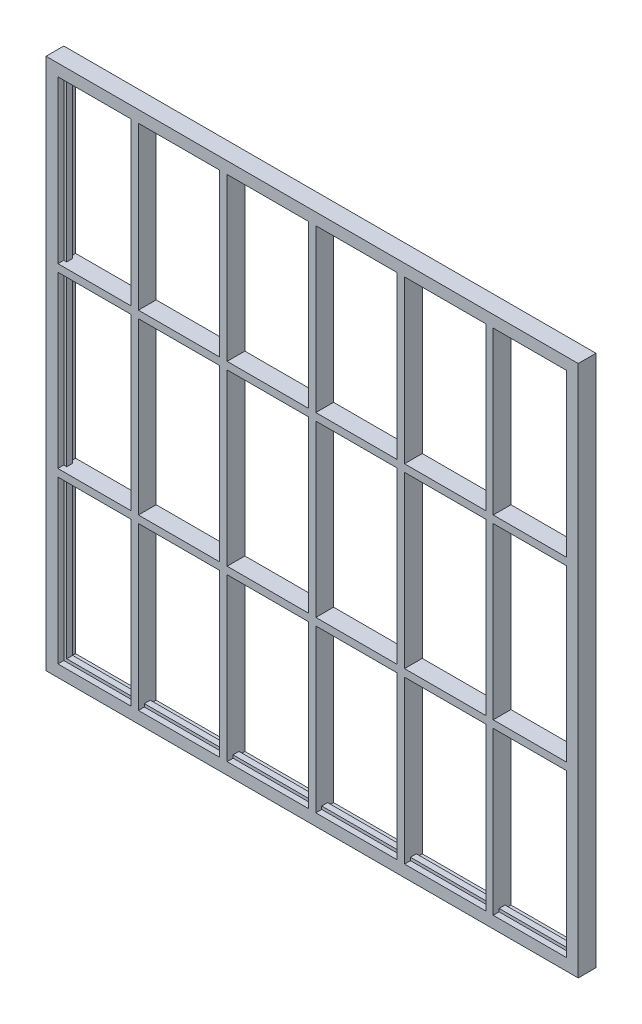
SolidWorks part; units mm, degrees
ref_plane "前视基准面" through (0, 0, 0) normal (0, 0, 1) x (1, 0, 0)
ref_plane "上视基准面" through (0, 0, 0) normal (0, 1, 0) x (1, 0, 0)
ref_plane "右视基准面" through (0, 0, 0) normal (1, 0, 0) x (0, 0, -1)
sketch "草图1" plane through (0, 0, 0) normal (1, 0, 0) x (0, 0, -1)
  line L0 (30, 0) -> (-30, 0)
  line L1 (-30, 0) -> (-30, 40)
  line L2 (-30, 40) -> (-10, 40)
  line L3 (-10, 40) -> (-10, 50)
  line L4 (-10, 50) -> (10, 50)
  line L5 (0, 0) -> (0, 164.1985) construction
  line L6 (10, 40) -> (10, 50)
  line L7 (30, 40) -> (10, 40)
  line L8 (30, 0) -> (30, 40)
  line L9 (-155.4817, 900) -> (236.5603, 900) construction
  line L10 (30, 1800) -> (30, 1760)
  line L11 (30, 1760) -> (10, 1760)
  line L12 (10, 1760) -> (10, 1750)
  line L13 (-10, 1750) -> (10, 1750)
  line L14 (-10, 1760) -> (-10, 1750)
  line L15 (-30, 1760) -> (-10, 1760)
  line L16 (-30, 1800) -> (-30, 1760)
  line L17 (30, 1800) -> (-30, 1800)
  point P9 (0, 50)
  point P22 (0, 1750)
  dimension "D1" = 60
  dimension "D2" = 40
  dimension "D3" = 50
  dimension "D4" = 900
  dimension "D5" = 20
extrude "凸台-拉伸1" add sketch "草图1" along normal mid plane 1800
sketch "草图3" plane through (0, 1760, 0) normal (0, -1, 0) x (1, 0, 0)
  line L0 (-900, -30) -> (-900, 30)
  line L1 (-900, 30) -> (-860, 30)
  line L2 (900, 30) -> (-900, 30) construction
  line L3 (-860, 30) -> (-860, 10)
  line L4 (-860, 10) -> (-850, 10)
  line L5 (-850, 10) -> (-850, -10)
  line L6 (-850, -10) -> (-860, -10)
  line L7 (-860, -10) -> (-860, -30)
  line L8 (900, -30) -> (-900, -30) construction
  line L9 (-860, -30) -> (-900, -30)
  line L10 (-900, 0) -> (-1150.2083, 0) construction
  line L11 (0, 0) -> (0, 199.5388) construction
  line L12 (900, 0) -> (1150.2083, 0) construction
  line L13 (860, -30) -> (900, -30)
  line L14 (860, -10) -> (860, -30)
  line L15 (850, -10) -> (860, -10)
  line L16 (850, 10) -> (850, -10)
  line L17 (860, 10) -> (850, 10)
  line L18 (860, 30) -> (860, 10)
  line L19 (900, 30) -> (860, 30)
  line L20 (900, -30) -> (900, 30)
  dimension "D1" = 40
  dimension "D2" = 50
  dimension "D3" = 20
extrude "凸台-拉伸2" add sketch "草图3" along normal up to surface (1720 mm away) separate body up to face at (0, 40, 20)
sketch "草图4" plane through (0, 1760, 0) normal (0, -1, 0) x (1, 0, 0)
  line L0 (900, -30) -> (-900, -30) construction
  line L1 (-900, 30) -> (-850, 30)
  line L2 (-900, 30) -> (-900, -30)
  line L3 (-900, -30) -> (-850, -30)
  line L4 (-850, 30) -> (-850, -30)
  line L5 (0, 0) -> (0, 218.547) construction
  line L6 (850, 30) -> (850, -30)
  line L7 (900, -30) -> (850, -30)
  line L8 (900, 30) -> (900, -30)
  line L9 (900, 30) -> (850, 30)
  dimension "D1" = 50
extrude "切除-拉伸1" cut sketch "草图4" along normal blind 10
sketch "草图5" plane through (0, 40, 0) normal (0, 1, 0) x (1, 0, 0)
  line L0 (900, -30) -> (-900, -30) construction
  line L1 (-900, 30) -> (-850, 30)
  line L2 (-900, 30) -> (-900, -30)
  line L3 (-900, -30) -> (-850, -30)
  line L4 (-850, 30) -> (-850, -30)
  line L5 (0, 0) -> (0, 304.5992) construction
  line L6 (850, 30) -> (850, -30)
  line L7 (900, -30) -> (850, -30)
  line L8 (900, 30) -> (900, -30)
  line L9 (900, 30) -> (850, 30)
  dimension "50" = 50
extrude "切除-拉伸2" cut sketch "草图5" along normal blind 10
sketch "草图6" plane through (860, 0, 0) normal (-1, 0, 0) x (0, 0, 1)
  line L0 (30, 40) -> (30, 1760) construction
  line L1 (-30, 1212.5) -> (30, 1212.5)
  line L2 (-30, 1212.5) -> (-30, 1187.5)
  line L3 (-30, 1187.5) -> (30, 1187.5)
  line L4 (30, 1212.5) -> (30, 1187.5)
  line L5 (-30, 1212.5) -> (30, 1187.5) construction
  line L6 (-30, 1187.5) -> (30, 1212.5) construction
  line L7 (-30, 1800) -> (30, 1800) construction
  point P0 (0, 1200)
  dimension "D1" = 25
  dimension "D2" = 600
extrude "凸台-拉伸3" add sketch "草图6" along normal up to surface (1720 mm away) up to face at (-860, 900, 20)
pattern_linear "阵列(线性)1" count 2 spacing 600 along (0, -1, 0) of "凸台-拉伸3"
sketch "草图7" plane through (0, 1760, 0) normal (0, -1, 0) x (1, 0, 0)
  line L0 (900, 30) -> (-900, 30) construction
  line L1 (-612.5, -30) -> (-587.5, -30)
  line L2 (-612.5, -30) -> (-612.5, 30)
  line L3 (-612.5, 30) -> (-587.5, 30)
  line L4 (-587.5, -30) -> (-587.5, 30)
  line L5 (-612.5, -30) -> (-587.5, 30) construction
  line L6 (-612.5, 30) -> (-587.5, -30) construction
  line L7 (-900, 30) -> (-900, -30) construction
  point P0 (-600, 0)
  dimension "D1" = 300
  dimension "D2" = 25
extrude "凸台-拉伸4" add sketch "草图7" along normal blind 1729
pattern_linear "阵列(线性)2" count 5 spacing 300 along (1, 0, 0) of "凸台-拉伸4"
